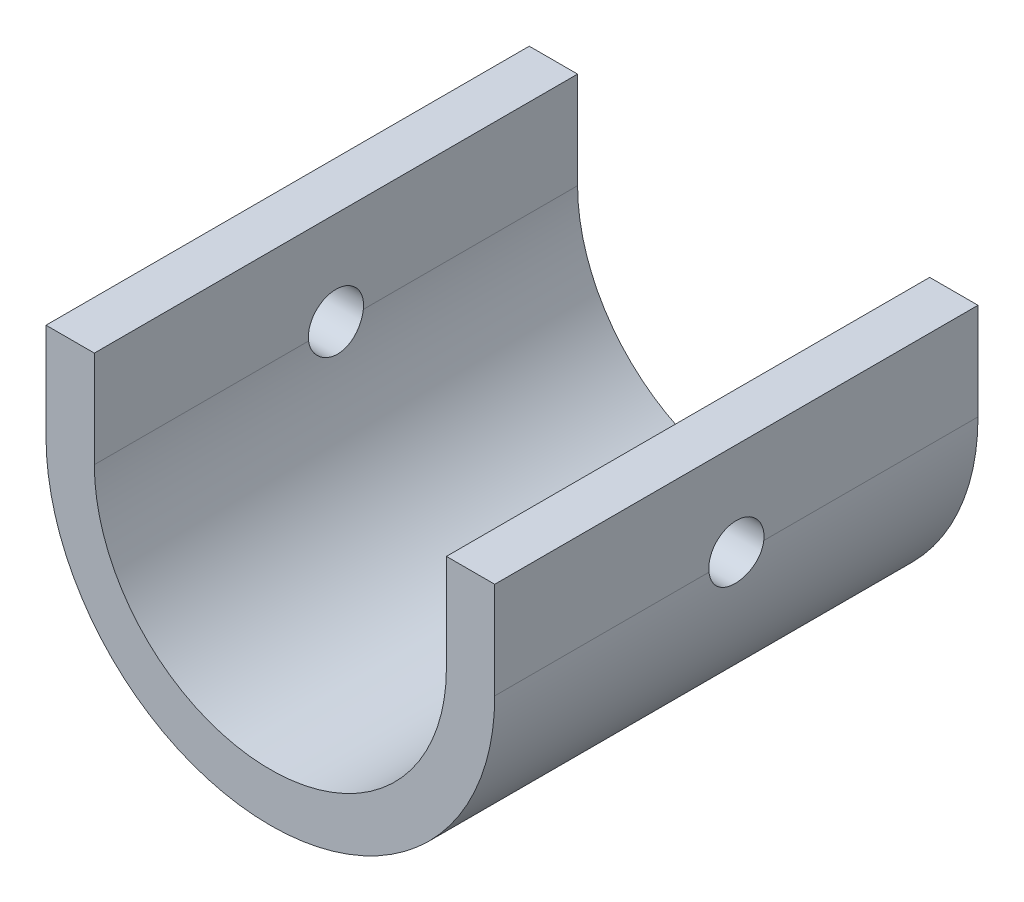
SolidWorks part; units mm, degrees
material "BUTYL"
ref_plane "Front Plane" through (0, 0, 0) normal (0, 0, 1) x (1, 0, 0)
ref_plane "Top Plane" through (0, 0, 0) normal (0, 1, 0) x (1, 0, 0)
ref_plane "Right Plane" through (0, 0, 0) normal (1, 0, 0) x (0, 0, -1)
sketch "Sketch1" plane through (0, 0, 0) normal (0, 0, 1) x (1, 0, 0)
  circle A0 centre (0, 0) radius 16.25
extrude "Boss-Extrude1" add sketch "Sketch1" against normal blind 35 contours A0
sketch "Sketch2" plane through (0, 0, 0) normal (0, 0, 1) x (1, 0, 0)
  circle A0 centre (0, 0) radius 12.75
  circle A1 centre (0, 0) radius 16.25 construction
  dimension "D1" = 3.5
extrude "Cut-Extrude1" cut sketch "Sketch2" against normal blind 35
sketch "Sketch3" plane through (0, 0, 0) normal (0, 0, 1) x (1, 0, 0)
  circle A0 centre (0, 0) radius 12.75
ref_plane "Plane1" through (0, 0, -17.5) normal (0, 0, 1) x (1, 0, 0)
sketch "Sketch7" plane through (0, 0, -17.5) normal (0, 0, 1) x (1, 0, 0)
  line L0 (55, 0) -> (-55, 0) construction
  line L1 (16.25, 0) -> (-16.47, 0)
  line L2 (16.25, 0) -> (16.25, 16.591)
  line L3 (16.25, 16.591) -> (-16.47, 16.591)
  line L4 (-16.47, 0) -> (-16.47, 16.591)
  circle A0 centre (0, 0) radius 16.25 construction
extrude "Cut-Extrude2" cut sketch "Sketch7" against normal mid plane 35
sketch "Sketch9" plane through (0, 0, 0) normal (0, 1, 0) x (1, 0, 0)
  line L0 (-44.2539, 0) -> (44.2539, 0) construction
  line L1 (-16.25, 35) -> (16.25, 35)
  line L2 (-16.25, 35) -> (-16.25, 0)
  line L3 (-16.25, 0) -> (16.25, 0)
  line L4 (16.25, 35) -> (16.25, 0)
  line L5 (16.25, 35) -> (16.25, 0) construction
sketch "Sketch10" plane through (0, 0, 0) normal (0, 1, 0) x (1, 0, 0)
  line L0 (-12.75, 0) -> (12.75, 0) construction
  line L1 (12.75, 0) -> (-12.75, 0)
  line L2 (12.75, 0) -> (12.75, 35)
  line L3 (12.75, 35) -> (-12.75, 35)
  line L4 (-12.75, 0) -> (-12.75, 35)
  line L5 (12.75, 0) -> (12.75, 35) construction
extrude "Boss-Extrude2" add sketch "Sketch9" along normal blind 7
extrude "Cut-Extrude3" cut sketch "Sketch10" along normal blind 7
ref_plane "Plane2" through (0, 7, 0) normal (0, 1, 0) x (1, 0, 0)
ref_plane "Plane3" through (0, 0.25, 0) normal (0, 1, 0) x (1, 0, 0)
ref_plane "Plane4" through (16.25, 0, 0) normal (1, 0, 0) x (0, 0, -1)
ref_plane "Plane5" through (-16.25, 0, 0) normal (1, 0, 0) x (0, 0, -1)
sketch "Sketch14" plane through (16.25, 0, 0) normal (1, 0, 0) x (0, 0, -1)
  line L0 (29.1433, 0.25) -> (-29.1433, 0.25) construction
  line L1 (17.5, 12.7875) -> (17.5, -12.7875) construction
  circle A0 centre (17.5, 0.25) radius 2
sketch "Sketch15" plane through (-16.25, 0, 0) normal (1, 0, 0) x (0, 0, -1)
  circle A0 centre (17.5, 0.25) radius 2
extrude "Cut-Extrude5" cut sketch "Sketch15" along normal blind 4 contours A0
extrude "Cut-Extrude6" cut sketch "Sketch14" against normal blind 4
